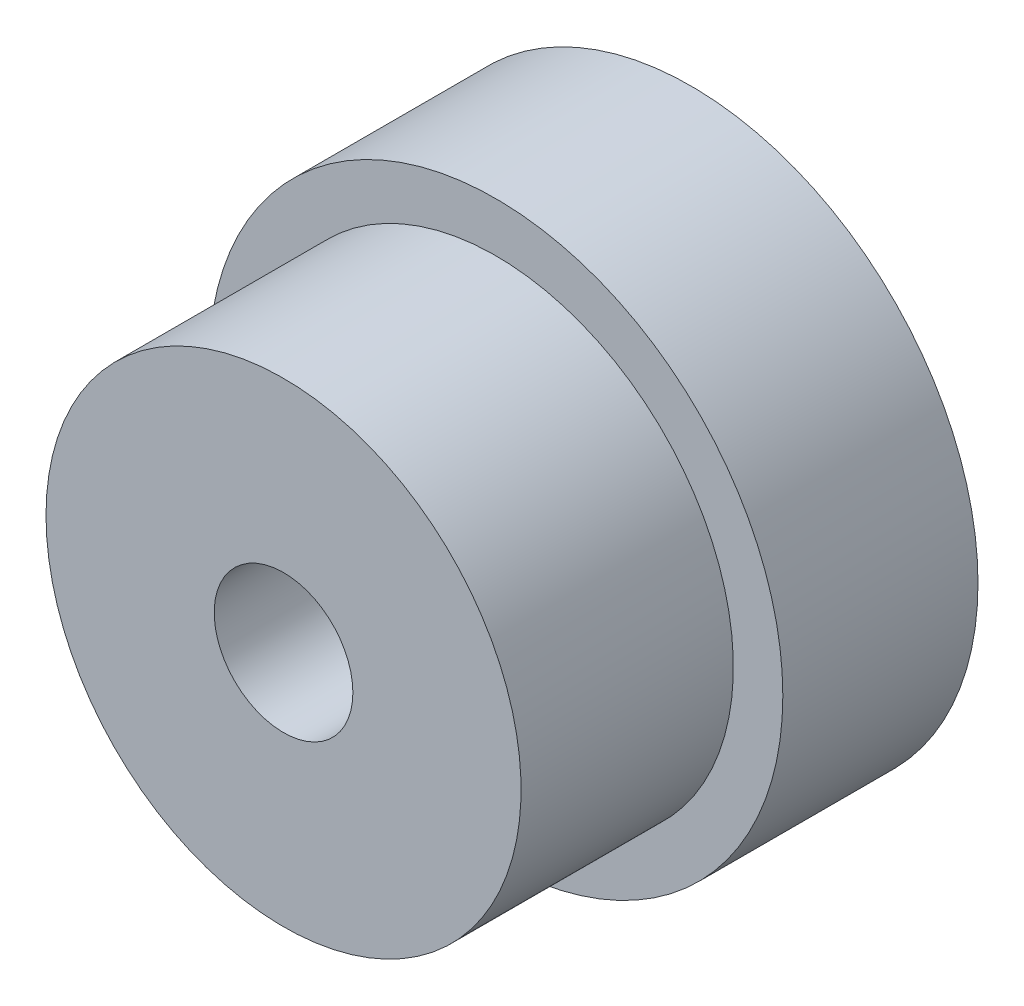
SolidWorks part; units mm, degrees
ref_plane "Alzado" through (0, 0, 0) normal (0, 0, 1) x (1, 0, 0)
ref_plane "Planta" through (0, 0, 0) normal (0, 1, 0) x (1, 0, 0)
ref_plane "Vista lateral" through (0, 0, 0) normal (1, 0, 0) x (0, 0, -1)
sketch "Croquis1" plane through (0, 0, 0) normal (0, 0, 1) x (1, 0, 0)
  circle A0 centre (0, 0) radius 16.765
  dimension "D1" = 33.53
extrude "Saliente-Extruir1" add sketch "Croquis1" along normal blind 11.4
sketch "Croquis2" plane through (0, 0, 11.4) normal (0, 0, 1) x (1, 0, 0)
  circle A0 centre (0, 0) radius 13.875
  dimension "D1" = 27.75
extrude "Saliente-Extruir2" add sketch "Croquis2" along normal blind 12.4
sketch "Croquis3" plane through (0, 0, 23.8) normal (0, 0, 1) x (1, 0, 0)
  circle A0 centre (0, 0) radius 4.05
extrude "Cortar-Extruir1" cut sketch "Croquis3" against normal blind 32.4
